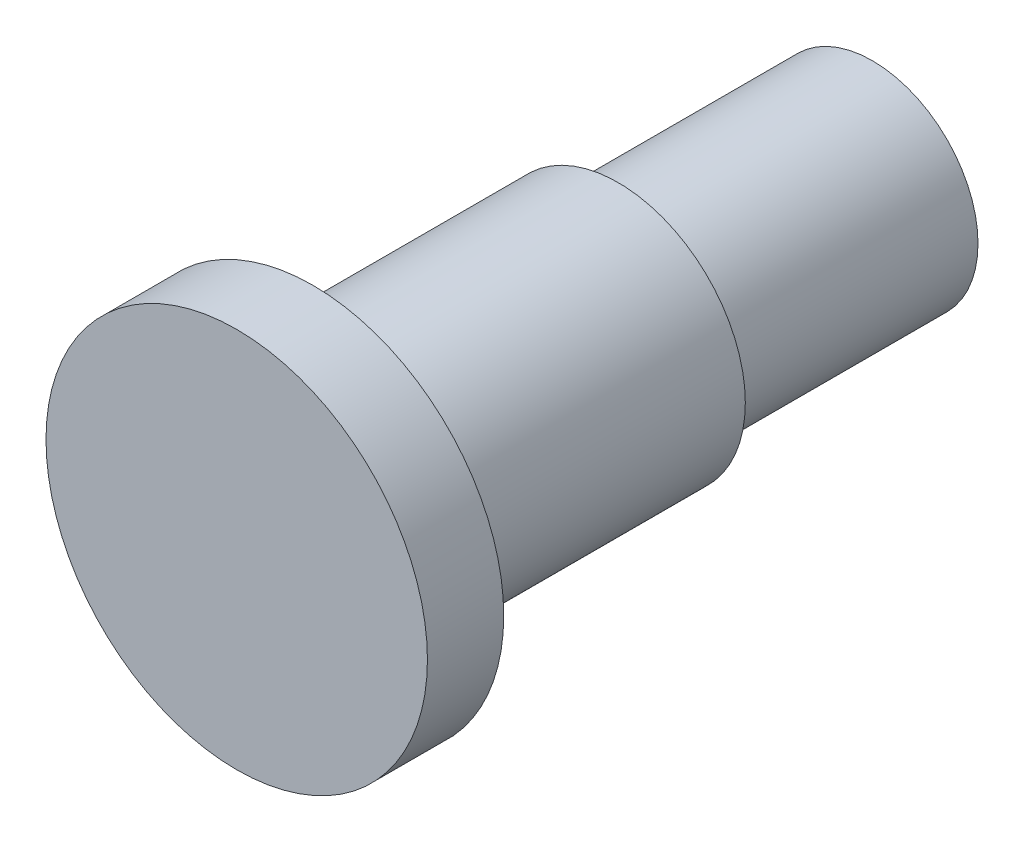
SolidWorks part; units mm, degrees
ref_plane "Front Plane" through (0, 0, 0) normal (0, 0, 1) x (1, 0, 0)
ref_plane "Top Plane" through (0, 0, 0) normal (0, 1, 0) x (1, 0, 0)
ref_plane "Right Plane" through (0, 0, 0) normal (1, 0, 0) x (0, 0, -1)
sketch "Sketch1" plane through (0, 0, 0) normal (0, 0, 1) x (1, 0, 0)
  circle A0 centre (0, 0) radius 4.15
extrude "M10 rod engagement, thread core represented" add sketch "Sketch1" along normal blind 10 from offset 10
sketch "Sketch2" plane through (0, 0, 0) normal (0, 0, 1) x (1, 0, 0)
  circle A0 centre (0, 0) radius 5
extrude "Floating shoulder through bridge" add sketch "Sketch2" along normal blind 12
sketch "Sketch3" plane through (0, 0, 0) normal (0, 0, 1) x (1, 0, 0)
  circle A0 centre (0, 0) radius 7.5
extrude "Captive thrust head" add sketch "Sketch3" along normal blind 3 from offset 12
